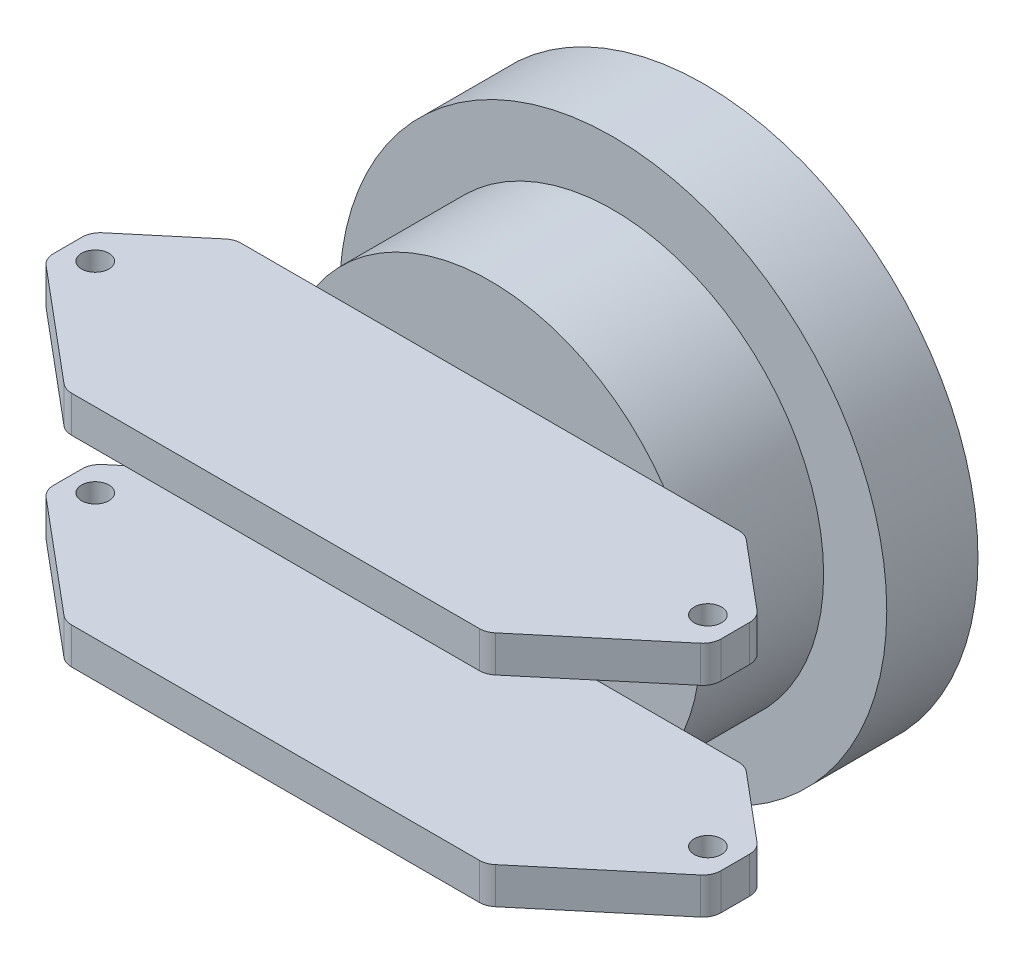
SolidWorks part; units mm, degrees
material "AISI 347 Annealed Stainless Steel (SS)"
ref_plane "Front" through (0, 0, 0) normal (0, 0, 1) x (1, 0, 0)
ref_plane "Top" through (0, 0, 0) normal (0, 1, 0) x (1, 0, 0)
ref_plane "Right" through (0, 0, 0) normal (1, 0, 0) x (0, 0, -1)
sketch "Sketch1" plane through (0, 0, 0) normal (0, 0, 1) x (1, 0, 0)
  circle A0 centre (0, 0) radius 30
  dimension "D1" = 60
extrude "Boss-Extrude1" add sketch "Sketch1" along normal blind 10
sketch "Sketch2" plane through (0, 0, 10) normal (0, 0, 1) x (1, 0, 0)
  circle A0 centre (0, 0) radius 23.08
extrude "Boss-Extrude2" add sketch "Sketch2" along normal blind 13.4862 contours A0
ref_plane "Plane1" through (0, 13, 0) normal (0, 1, 0) x (1, 0, 0)
sketch "Sketch4" plane through (0, 13, 0) normal (0, 1, 0) x (1, 0, 0)
  line L0 (0, -23.4862) -> (-48.9101, -23.4862) construction
  line L1 (-23.08, -23.4862) -> (23.08, -23.4862) construction
  line L2 (28, -23.4862) -> (-28, -23.4862)
  line L3 (-28, -23.4862) -> (-36.5797, -30.6854)
  line L4 (-36.5797, -30.6854) -> (-36.5797, -35.6854)
  line L5 (-23.08, -23.4862) -> (-23.08, -83.02) construction
  line L6 (-23.08, -10) -> (-23.08, -23.4862) construction
  line L7 (-36.5797, -35.6854) -> (-23.08, -47.013)
  line L8 (-36.5797, -35.6854) -> (-36.5797, -54.4246) construction
  line L9 (-23.08, -47.013) -> (23.08, -47.013)
  line L10 (0, -23.4862) -> (0, -50.8219) construction
  line L11 (36.5797, -35.6854) -> (23.08, -47.013)
  line L12 (36.5797, -30.6854) -> (36.5797, -35.6854)
  line L13 (28, -23.4862) -> (36.5797, -30.6854)
  point P17 (0, -47.013)
  dimension "D1" = 28
  dimension "D2" = 40
  dimension "D3" = 5
  dimension "D4" = 11.2
  dimension "D5" = 50
extrude "Boss-Extrude3" add sketch "Sketch4" against normal blind 4
fillet "Fillet1" radius 2 8 edges at (-28, 11, 23.4862) (28, 11, 23.4862) (36.5797, 11, 30.6854) (36.5797, 11, 35.6854) (23.08, 11, 47.013) (-23.08, 11, 47.013) (-36.5797, 11, 35.6854) (-36.5797, 11, 30.6854)
sketch "Sketch5" plane through (0, 13, 0) normal (0, 1, 0) x (1, 0, 0)
  line L0 (-36.5797, -33.1854) -> (-33.5797, -33.1854) construction
  line L1 (-36.5797, -31.618) -> (-36.5797, -34.7528) construction
  circle A0 centre (-33.5797, -33.1854) radius 1.5
  dimension "D2" = 3
  dimension "D1" = 3
extrude "Cut-Extrude1" cut sketch "Sketch5" against normal blind 4
mirror "Mirror1" about plane through (0, 0, 0) normal (1, 0, 0) of "Cut-Extrude1"
mirror "Mirror2" about plane through (0, 0, 0) normal (0, 1, 0) of "Mirror1", "Cut-Extrude1", "Fillet1", "Boss-Extrude3"
sketch "Sketch8" plane through (0, 0, 0) normal (0, 0, -1) x (-1, 0, 0)
  circle A0 centre (0, 0) radius 7.5
  dimension "D1" = 15
extrude "Cut-Extrude2" cut sketch "Sketch8" against normal blind 10
ref_plane "Plane2" through (0, 0, -69) normal (0, 0, -1) x (-1, 0, 0)
sketch "Sketch9" plane through (0, 0, -69) normal (0, 0, -1) x (-1, 0, 0)
  line L0 (-159.6788, 0) -> (0, 0) construction
  line L1 (0, 0) -> (0, 159.6788) construction
  text T0 "X5\r\n" font "Century Gothic" height 20
  text T1 "Y5\r\n\r\n" font "Century Gothic" height 20
sketch "Sketch10" plane through (0, 0, 0) normal (0, 1, 0) x (1, 0, 0)
  line L0 (0, 69) -> (0, -23.3632) construction
  text T0 "Z5" font "Century Gothic" height 20
  point P0 (0, -23.3632)
ref_plane "Plane3" through (0, 0, 77.013) normal (0, 0, 1) x (1, 0, 0)
sketch "Sketch11" plane through (0, 0, 77.013) normal (0, 0, 1) x (1, 0, 0)
  line L0 (0, 159.6788) -> (0, 0) construction
  line L1 (0, 0) -> (159.6788, 0) construction
  line L2 (0, 0) -> (0, 159.6788) construction
  text T0 "X6" font "Century Gothic" height 20
  text T1 "Y6" font "Century Gothic" height 20
  point P2 (157.6068, 0)
sketch "Sketch12" plane through (0, 0, 0) normal (1, 0, 0) x (0, 0, -1)
  line L0 (-77.013, 0) -> (-236.6918, 0) construction
  line L1 (-77.013, 159.6788) -> (-77.013, 0) construction
  text T0 "Z6" font "Century Gothic" height 20
